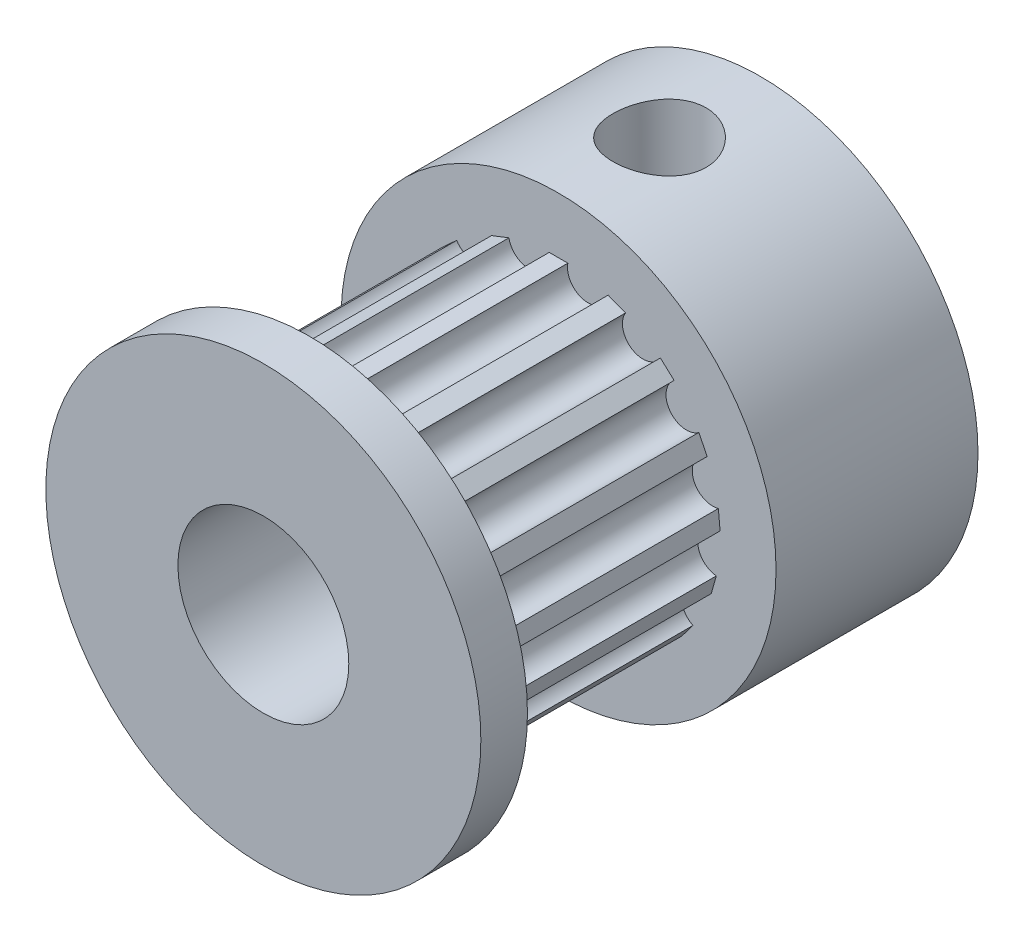
SolidWorks part; units mm, degrees
material "Alliage 1060"
ref_plane "Plan de face" through (0, 0, 0) normal (0, 0, 1) x (1, 0, 0)
ref_plane "Plan de dessus" through (0, 0, 0) normal (0, 1, 0) x (1, 0, 0)
ref_plane "Plan de droite" through (0, 0, 0) normal (1, 0, 0) x (0, 0, -1)
sketch "Esquisse1" plane through (0, 0, 0) normal (0, 0, 1) x (1, 0, 0)
  circle A0 centre (0, 0) radius 7
  dimension "D1" = 14
extrude "Boss.-Extru.1" add sketch "Esquisse1" along normal blind 6.5
sketch "Esquisse3" plane through (0, 0, 6.5) normal (0, 0, 1) x (1, 0, 0)
  line L0 (0, 0) -> (0, 7) construction
  line L1 (0, 5.1942) -> (0.3, 5.1942)
  line L2 (0, 5.1942) -> (-1.8764, 4.8435) construction
  line L3 (-1.8764, 4.8435) -> (-3.4993, 3.8386) construction
  line L4 (-3.4993, 3.8386) -> (-4.6497, 2.3153) construction
  line L5 (-4.6497, 2.3153) -> (-5.1721, 0.4793) construction
  line L6 (-5.1721, 0.4793) -> (-4.9959, -1.4215) construction
  line L7 (-4.9959, -1.4215) -> (-4.1451, -3.1302) construction
  line L8 (-4.1451, -3.1302) -> (-2.7344, -4.4162) construction
  line L9 (-2.7344, -4.4162) -> (-0.9544, -5.1058) construction
  line L10 (-0.9544, -5.1058) -> (0.9544, -5.1058) construction
  line L11 (0.9544, -5.1058) -> (2.7344, -4.4162) construction
  line L12 (2.7344, -4.4162) -> (4.1451, -3.1302) construction
  line L13 (4.1451, -3.1302) -> (4.9959, -1.4215) construction
  line L14 (4.9959, -1.4215) -> (5.1721, 0.4793) construction
  line L15 (5.1721, 0.4793) -> (4.6497, 2.3153) construction
  line L16 (4.6497, 2.3153) -> (3.4993, 3.8386) construction
  line L17 (3.4993, 3.8386) -> (1.8764, 4.8435) construction
  line L18 (1.8764, 4.8435) -> (0, 5.1942) construction
  line L19 (1.8764, 4.8435) -> (1.5966, 4.9518)
  line L20 (0, 0) -> (1.8764, 4.8435) construction
  line L21 (0.3, 5.1942) -> (1.5966, 4.9518) construction
  line L22 (1.8764, 4.8435) -> (2.1561, 4.7351)
  line L23 (3.4993, 3.8386) -> (3.2776, 4.0407)
  line L24 (3.4993, 3.8386) -> (3.721, 3.6365)
  line L25 (4.6497, 2.3153) -> (4.516, 2.5838)
  line L26 (4.6497, 2.3153) -> (4.7834, 2.0467)
  line L27 (5.1721, 0.4793) -> (5.1444, 0.778)
  line L28 (5.1721, 0.4793) -> (5.1997, 0.1805)
  line L29 (4.9959, -1.4215) -> (5.078, -1.1329)
  line L30 (4.9959, -1.4215) -> (4.9138, -1.71)
  line L31 (4.1451, -3.1302) -> (4.3259, -2.8908)
  line L32 (4.1451, -3.1302) -> (3.9643, -3.3696)
  line L33 (2.7344, -4.4162) -> (2.9895, -4.2583)
  line L34 (2.7344, -4.4162) -> (2.4793, -4.5741)
  line L35 (0.9544, -5.1058) -> (1.2493, -5.0507)
  line L36 (0.9544, -5.1058) -> (0.6595, -5.1609)
  line L37 (-0.9544, -5.1058) -> (-0.6595, -5.1609)
  line L38 (-0.9544, -5.1058) -> (-1.2493, -5.0507)
  line L39 (-2.7344, -4.4162) -> (-2.4793, -4.5741)
  line L40 (-2.7344, -4.4162) -> (-2.9895, -4.2583)
  line L41 (-4.1451, -3.1302) -> (-3.9643, -3.3696)
  line L42 (-4.1451, -3.1302) -> (-4.3259, -2.8908)
  line L43 (-4.9959, -1.4215) -> (-4.9138, -1.71)
  line L44 (-4.9959, -1.4215) -> (-5.078, -1.1329)
  line L45 (-5.1721, 0.4793) -> (-5.1997, 0.1805)
  line L46 (-5.1721, 0.4793) -> (-5.1444, 0.778)
  line L47 (-4.6497, 2.3153) -> (-4.7834, 2.0467)
  line L48 (-4.6497, 2.3153) -> (-4.516, 2.5838)
  line L49 (-3.4993, 3.8386) -> (-3.721, 3.6365)
  line L50 (-3.4993, 3.8386) -> (-3.2776, 4.0407)
  line L51 (-1.8764, 4.8435) -> (-2.1561, 4.7351)
  line L52 (-1.8764, 4.8435) -> (-1.5966, 4.9518)
  line L53 (0, 5.1942) -> (-0.3, 5.1942)
  circle A0 centre (0, 0) radius 7 construction
  circle A1 centre (0, 0) radius 5.1058 construction
  arc A2 (0.3, 5.1942) -> (1.5966, 4.9518) centre (0.9483, 5.073) ccw
  arc A3 (2.1561, 4.7351) -> (3.2776, 4.0407) centre (2.7169, 4.3879) ccw
  arc A4 (3.721, 3.6365) -> (4.516, 2.5838) centre (4.1185, 3.1101) ccw
  arc A5 (4.7834, 2.0467) -> (5.1444, 0.778) centre (4.9639, 1.4123) ccw
  arc A6 (5.1997, 0.1805) -> (5.078, -1.1329) centre (5.1389, -0.4762) ccw
  arc A7 (4.9138, -1.71) -> (4.3259, -2.8908) centre (4.6199, -2.3004) ccw
  arc A8 (3.9643, -3.3696) -> (2.9895, -4.2583) centre (3.4769, -3.814) ccw
  arc A9 (2.4793, -4.5741) -> (1.2493, -5.0507) centre (1.8643, -4.8124) ccw
  arc A10 (0.6595, -5.1609) -> (-0.6595, -5.1609) centre (0, -5.1609) ccw
  arc A11 (-1.2493, -5.0507) -> (-2.4793, -4.5741) centre (-1.8643, -4.8124) ccw
  arc A12 (-2.9895, -4.2583) -> (-3.9643, -3.3696) centre (-3.4769, -3.814) ccw
  arc A13 (-4.3259, -2.8908) -> (-4.9138, -1.71) centre (-4.6199, -2.3004) ccw
  arc A14 (-5.078, -1.1329) -> (-5.1997, 0.1805) centre (-5.1389, -0.4762) ccw
  arc A15 (-5.1444, 0.778) -> (-4.7834, 2.0467) centre (-4.9639, 1.4123) ccw
  arc A16 (-4.516, 2.5838) -> (-3.721, 3.6365) centre (-4.1185, 3.1101) ccw
  arc A17 (-3.2776, 4.0407) -> (-2.1561, 4.7351) centre (-2.7169, 4.3879) ccw
  arc A18 (-1.5966, 4.9518) -> (-0.3, 5.1942) centre (-0.9483, 5.073) ccw
  point P27 (0.971, 5.1942)
  dimension "D3" = 17
  dimension "D1" = 10.3
  dimension "D2" = 0.3
extrude "Boss.-Extru.2" add sketch "Esquisse3" along normal blind 8
sketch "Esquisse4" plane through (0, 0, 14.5) normal (0, 0, 1) x (1, 0, 0)
  circle A0 centre (0, 0) radius 7
  circle A1 centre (0, 0) radius 7 construction
extrude "Boss.-Extru.3" add sketch "Esquisse4" along normal blind 1.5
sketch "Esquisse5" plane through (0, 0, 0) normal (0, 0, -1) x (-1, 0, 0)
  circle A0 centre (0, 0) radius 2.75
  dimension "D1" = 5.5
extrude "Enlèv. mat.-Extru.1" cut sketch "Esquisse5" against normal up to surface (16 mm away) up to face at (7, 0, 16)
sketch "Esquisse8" plane through (0, 0, 0) normal (0, 1, 0) x (1, 0, 0)
  line L0 (-7, 0) -> (-7, -6.5) construction
  circle A0 centre (0, -3.25) radius 1.5
  point P2 (-7, -3.25)
  dimension "D1" = 3
extrude "Enlèv. mat.-Extru.3" cut sketch "Esquisse8" along normal up to surface (7 mm away)
sketch3d "Esquisse3D1" plane through (0, 0, 0) normal (0, 0, 1) x (1, 0, 0)
  dimension "D1" = 2
sketch "Esquisse10" plane through (0, 0, -2) normal (0, 0, -1) x (-1, 0, 0)
  line L0 (-8, 12) -> (-8, -8) construction
  line L1 (-8, -8) -> (12, -8) construction
  dimension "D1" = 8
  dimension "D2" = 8
  dimension "D3" = 20
  dimension "D4" = 20
